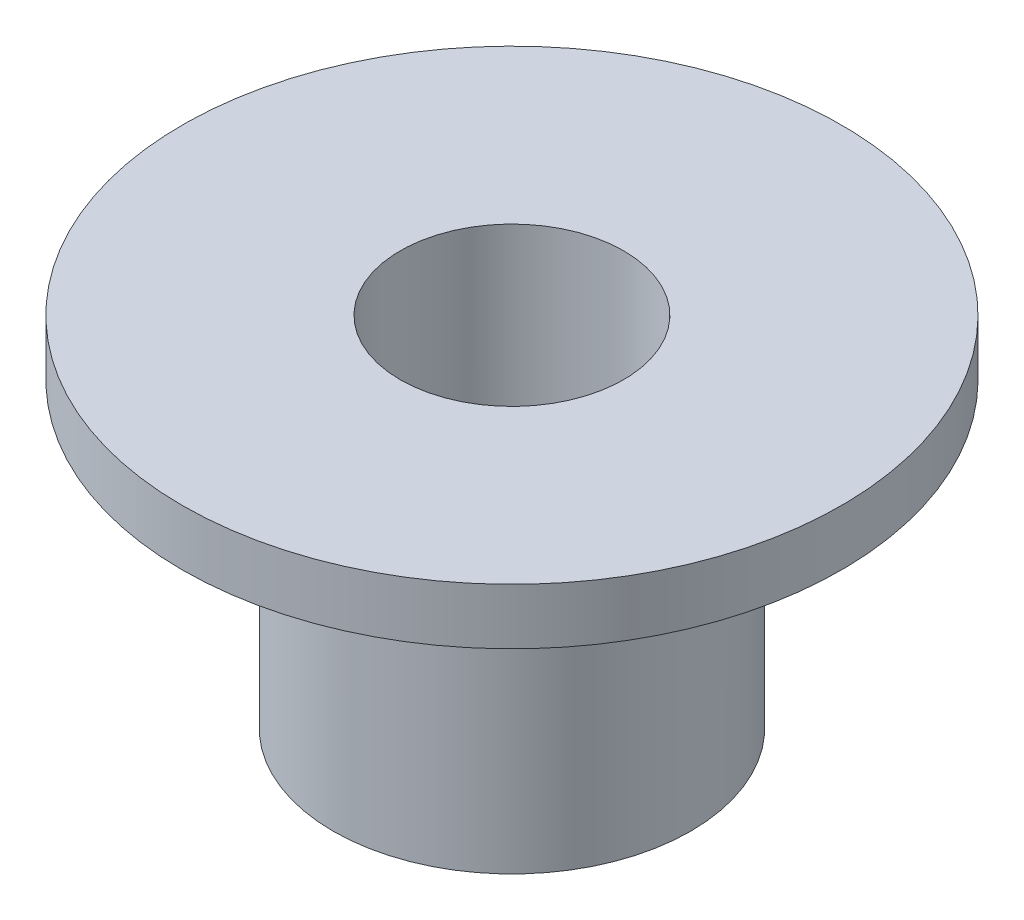
SolidWorks part; units mm, degrees
ref_plane "Front Plane" through (0, 0, 0) normal (0, 0, 1) x (1, 0, 0)
ref_plane "Top Plane" through (0, 0, 0) normal (0, 1, 0) x (1, 0, 0)
ref_plane "Right Plane" through (0, 0, 0) normal (1, 0, 0) x (0, 0, -1)
sketch "Sketch1" plane through (0, 0, 0) normal (0, 1, 0) x (1, 0, 0)
  circle A0 centre (0, 0) radius 29.5
  circle A1 centre (0, 0) radius 10
extrude "Boss-Extrude1" add sketch "Sketch1" along normal blind 5
sketch "Sketch2" plane through (0, 0, 0) normal (0, -1, 0) x (-1, 0, 0)
  circle A0 centre (0, 0) radius 16
  circle A1 centre (0, 0) radius 10
extrude "Boss-Extrude2" add sketch "Sketch2" along normal blind 27
